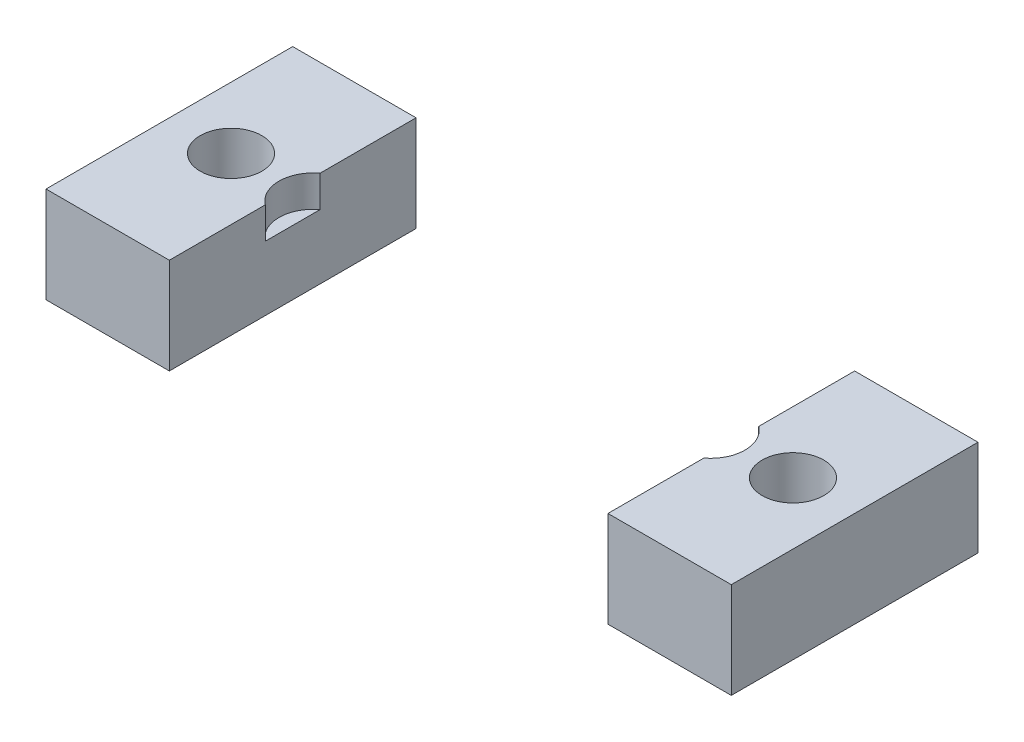
SolidWorks part; units mm, degrees
material "PVC 0.007 Plasticized"
ref_plane "Front Plane" through (0, 0, 0) normal (0, 0, 1) x (1, 0, 0)
ref_plane "Top Plane" through (0, 0, 0) normal (0, 1, 0) x (1, 0, 0)
ref_plane "Right Plane" through (0, 0, 0) normal (1, 0, 0) x (0, 0, -1)
sketch "Sketch1" plane through (0, 0, 0) normal (0, 1, 0) x (1, 0, 0)
  line L1 (0, 0) -> (50, 0)
  line L2 (0, 0) -> (0, 18)
  line L3 (0, 18) -> (50, 18)
  line L4 (50, 0) -> (50, 18)
  dimension "D1" = 50
  dimension "D2" = 18
extrude "Boss-Extrude2" add sketch "Sketch1" along normal blind 22
sketch "Sketch4" plane through (0, 0, 0) normal (0, 0, 1) x (1, 0, 0)
  line L0 (25, 0) -> (25, 22) construction
  line L1 (0, 0) -> (50, 0) construction
  line L2 (0, 22) -> (50, 22) construction
  line L4 (9, -7) -> (41, -7)
  line L5 (9, -7) -> (9, 7)
  line L6 (9, 7) -> (41, 7)
  line L7 (41, -7) -> (41, 7)
  line L8 (9, -7) -> (41, 7) construction
  line L9 (9, 7) -> (41, -7) construction
  dimension "D1" = 32
  dimension "D2" = 14
extrude "Cut-Extrude1" cut sketch "Sketch4" against normal through all
sketch "Sketch5" plane through (0, 0, -18) normal (0, 0, -1) x (-1, 0, 0)
  line L0 (-25, 7) -> (-25, 22) construction
  line L1 (-41, 7) -> (-9, 7) construction
  line L2 (-50, 22) -> (0, 22) construction
  line L4 (-36.5, -2) -> (-13.5, -2)
  line L5 (-36.5, -2) -> (-36.5, 16)
  line L6 (-36.5, 16) -> (-13.5, 16)
  line L7 (-13.5, -2) -> (-13.5, 16)
  line L8 (-36.5, -2) -> (-13.5, 16) construction
  line L9 (-36.5, 16) -> (-13.5, -2) construction
  dimension "D1" = 23
  dimension "D2" = 18
extrude "Cut-Extrude3" cut sketch "Sketch5" against normal blind 13
sketch "Sketch7" plane through (0, 0, -18) normal (0, 0, -1) x (-1, 0, 0)
  line L0 (-50, 22) -> (-50, 0) construction
  line L1 (-50, 22) -> (0, 22)
  line L2 (-50, 22) -> (-50, 13.765)
  line L3 (-50, 13.765) -> (0, 13.765)
  line L4 (0, 22) -> (0, 13.765)
  line L5 (0, 22) -> (0, 0) construction
extrude "Cut-Extrude4" cut sketch "Sketch7" against normal through all
sketch "Sketch9" plane through (0, 7, 0) normal (0, -1, 0) x (1, 0, 0)
  circle A0 centre (12, -11.5) radius 1
  circle A1 centre (38, -11.5) radius 1
extrude "Cut-Extrude6" cut sketch "Sketch9" against normal through all
sketch "Sketch10" plane through (0, 13.765, 0) normal (0, 1, 0) x (1, 0, 0)
  line L0 (0, 9) -> (50, 9) construction
  line L1 (0, 0) -> (0, 18) construction
  line L2 (50, 0) -> (50, 18) construction
  line L3 (25, 9) -> (25, 20.1516) construction
  circle A0 centre (4.5, 9) radius 2.25
  circle A1 centre (45.5, 9) radius 2.25
  dimension "D1" = 4.5
  dimension "D2" = 4.5
extrude "Cut-Extrude7" cut sketch "Sketch10" against normal through all
sketch "Sketch11" plane through (0, 0, 0) normal (0, 0, 1) x (1, 0, 0)
  line L0 (9, 7) -> (50, 7)
  line L1 (50, 13.765) -> (50, 0) construction
  line L2 (50, 7) -> (50, 13.765)
  line L3 (50, 13.765) -> (0, 13.765)
  line L4 (0, 13.765) -> (0, 7)
  line L5 (0, 13.765) -> (0, 0) construction
  line L6 (0, 7) -> (9, 7)
extrude "Cut-Extrude8" cut sketch "Sketch11" against normal through all
sketch "Sketch14" plane through (0, 7, 0) normal (0, 1, 0) x (1, 0, 0)
  line L0 (41, 18) -> (41, 0) construction
  line L1 (9, 0) -> (41, 18) construction
  line L2 (41, 0) -> (9, 18) construction
  line L3 (9, 18) -> (41, 18) construction
  line L4 (41, 18) -> (25, 18) construction
  line L5 (25, 18) -> (25, 0) construction
  circle A0 centre (39.5, 9) radius 2.5
  circle A1 centre (45.5, 9) radius 2.25 construction
  circle A2 centre (10.5, 9) radius 2.5
  point P4 (41, 7)
  point P5 (41, 11)
  dimension "D1" = 5
  dimension "D2" = 6
extrude "Cut-Extrude10" cut sketch "Sketch14" against normal blind 2.3
